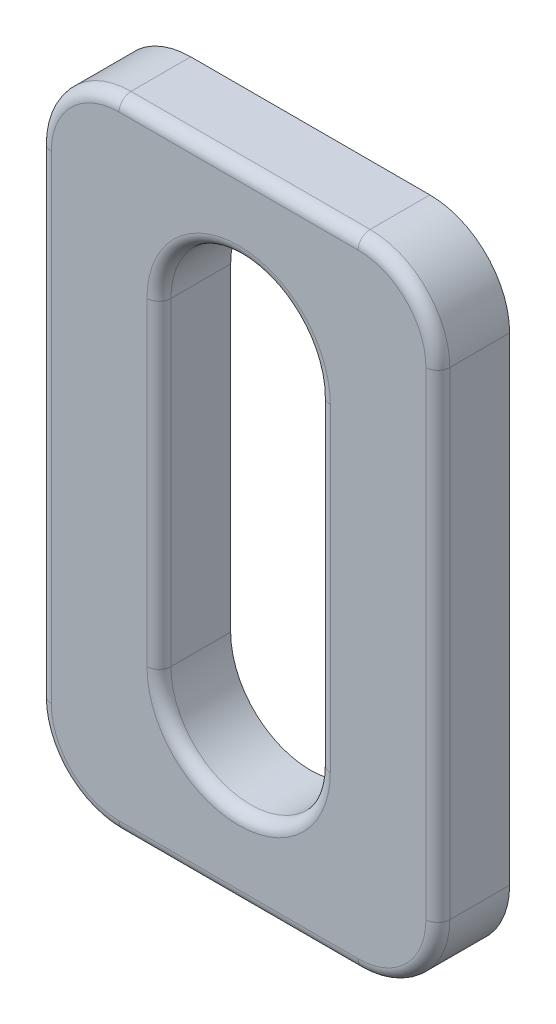
SolidWorks part; units mm, degrees
material "ABS"
ref_plane "Front Plane" through (0, 0, 0) normal (0, 0, 1) x (1, 0, 0)
ref_plane "Top Plane" through (0, 0, 0) normal (0, 1, 0) x (1, 0, 0)
ref_plane "Right Plane" through (0, 0, 0) normal (1, 0, 0) x (0, 0, -1)
sketch "Sketch1" plane through (0, 0, 0) normal (0, 0, 1) x (1, 0, 0)
  line L0 (12.5, 40) -> (12.5, 20) construction
  line L1 (0, 0) -> (25, 0)
  line L2 (0, 0) -> (0, 40)
  line L3 (0, 40) -> (25, 40)
  line L4 (25, 0) -> (25, 40)
  line L5 (12.5, 20) -> (12.5, 0) construction
  line L6 (12.5, 30) -> (12.5, 10) construction
  line L7 (17.5, 30) -> (17.5, 10)
  line L8 (7.5, 30) -> (7.5, 10)
  arc A0 (17.5, 30) -> (7.5, 30) centre (12.5, 30) ccw
  arc A1 (7.5, 10) -> (17.5, 10) centre (12.5, 10) ccw
  point P10 (12.5, 20)
  dimension "D3" = 5
  dimension "D1" = 25
  dimension "D2" = 40
extrude "Boss-Extrude1" add sketch "Sketch1" along normal blind 4.5
fillet "Fillet1" radius 5 4 edges at (25, 40, 2.25) (25, 0, 2.25) (0, 0, 2.25) (0, 40, 2.25)
fillet "Fillet2" radius 0.75 12 edges at (1.4645, 1.4645, 4.5) (0, 20, 4.5) (1.4645, 38.5355, 4.5) (23.5355, 38.5355, 4.5) (12.5, 40, 4.5) (25, 20, 4.5) (23.5355, 1.4645, 4.5) (12.5, 0, 4.5) (12.5, 5, 4.5) (17.5, 20, 4.5) (12.5, 35, 4.5) (7.5, 20, 4.5)
